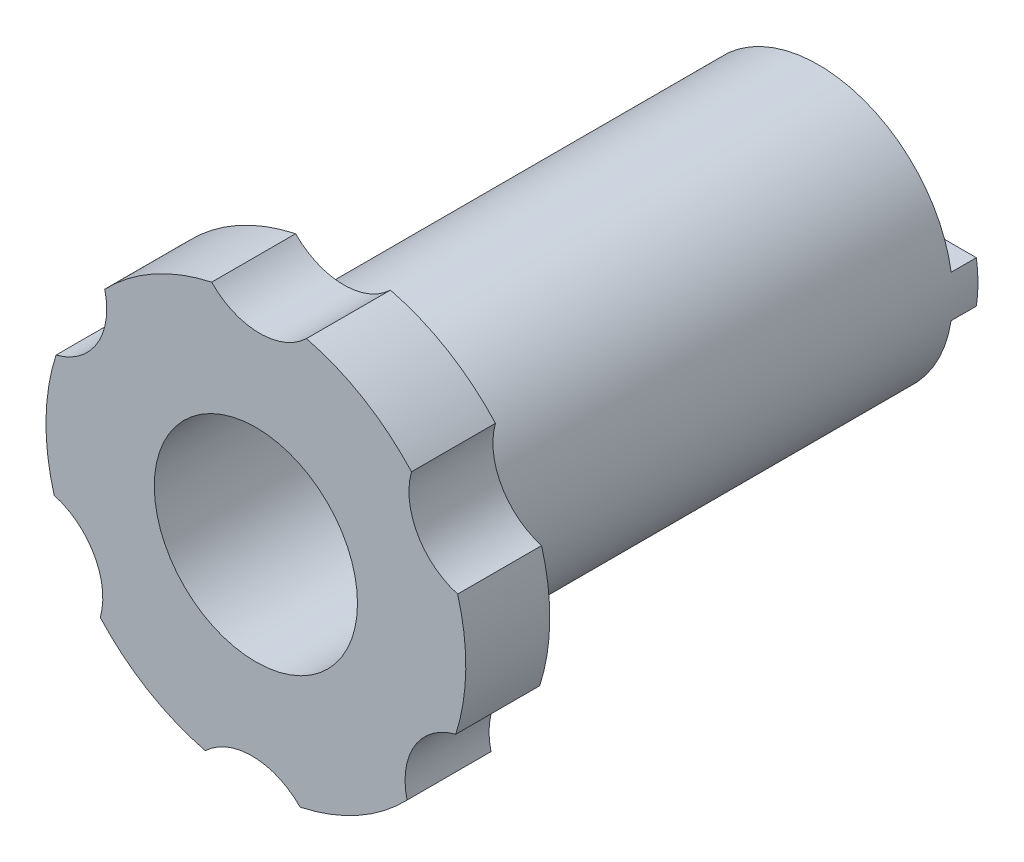
SolidWorks part; units mm, degrees
ref_plane "Front Plane" through (0, 0, 0) normal (1, 0, 0) x (0, 1, 0)
ref_plane "Top Plane" through (0, 0, 0) normal (0, 0, 1) x (0, 1, 0)
ref_plane "Right Plane" through (0, 0, 0) normal (0, 1, 0) x (-1, 0, 0)
sketch "Sketch1" plane through (0, 0, 0) normal (0, 0, 1) x (0, 1, 0)
  circle A0 centre (0, 0) radius 6.05
  circle A1 centre (0, 0) radius 8
  dimension "D1" = 12.1
  dimension "D2" = 16
extrude "Boss-Extrude1" add sketch "Sketch1" along normal blind 30
sketch "Sketch2" plane through (0, 0, 0) normal (1, 0, 0) x (0, 1, 0)
  line L0 (0, 0) -> (0, 30) construction
  line L1 (-8, 0) -> (8, 0) construction
  line L2 (6.05, 30) -> (-6.05, 30) construction
  line L3 (-8, 30) -> (-8, 0) construction
  line L4 (-8, 0) -> (-1.25, 0)
  line L5 (-8, 0) -> (-8, 1.5)
  line L6 (-8, 1.5) -> (-1.25, 1.5)
  line L7 (-1.25, 0) -> (-1.25, 1.5)
  line L8 (1.25, 1.5) -> (8, 1.5)
  line L9 (1.25, 1.5) -> (1.25, 0)
  line L10 (1.25, 0) -> (8, 0)
  line L11 (8, 1.5) -> (8, 0)
  dimension "D1" = 2.5
  dimension "D2" = 1.5
extrude "Cut-Extrude1" cut sketch "Sketch2" against normal through all both and the other way through all
sketch "Sketch3" plane through (0, 0, 30) normal (0, 0, 1) x (1, 0, 0)
  circle A0 centre (0, 0) radius 6.05
  circle A1 centre (0, 0) radius 12.5
  dimension "D1" = 12.1
  dimension "D2" = 25
extrude "Boss-Extrude2" add sketch "Sketch3" along normal blind 5
sketch "Sketch4" plane through (0, 0, 35) normal (0, 0, 1) x (1, 0, 0)
  line L0 (0.2325, 15.0093) -> (-0.2325, -15.0093) construction
  line L1 (-13.1147, -7.3033) -> (-0.2325, -15.0093) construction
  line L2 (-0.2325, -15.0093) -> (12.8822, -7.706) construction
  line L3 (12.8822, -7.706) -> (13.1147, 7.3033) construction
  line L4 (13.1147, 7.3033) -> (0.2325, 15.0093) construction
  line L5 (0.2325, 15.0093) -> (-12.8822, 7.706) construction
  line L6 (-12.8822, 7.706) -> (-13.1147, -7.3033) construction
  circle A1 centre (0, 0) radius 13 construction
  circle A2 centre (-12.8822, 7.706) radius 4
  circle A3 centre (0.2325, 15.0093) radius 4
  circle A4 centre (13.1147, 7.3033) radius 4
  circle A5 centre (12.8822, -7.706) radius 4
  circle A6 centre (-0.2325, -15.0093) radius 4
  circle A7 centre (-13.1147, -7.3033) radius 4
  dimension "D1" = 13
  dimension "D2" = 8
extrude "Cut-Extrude2" cut sketch "Sketch4" against normal through all both and the other way through all
